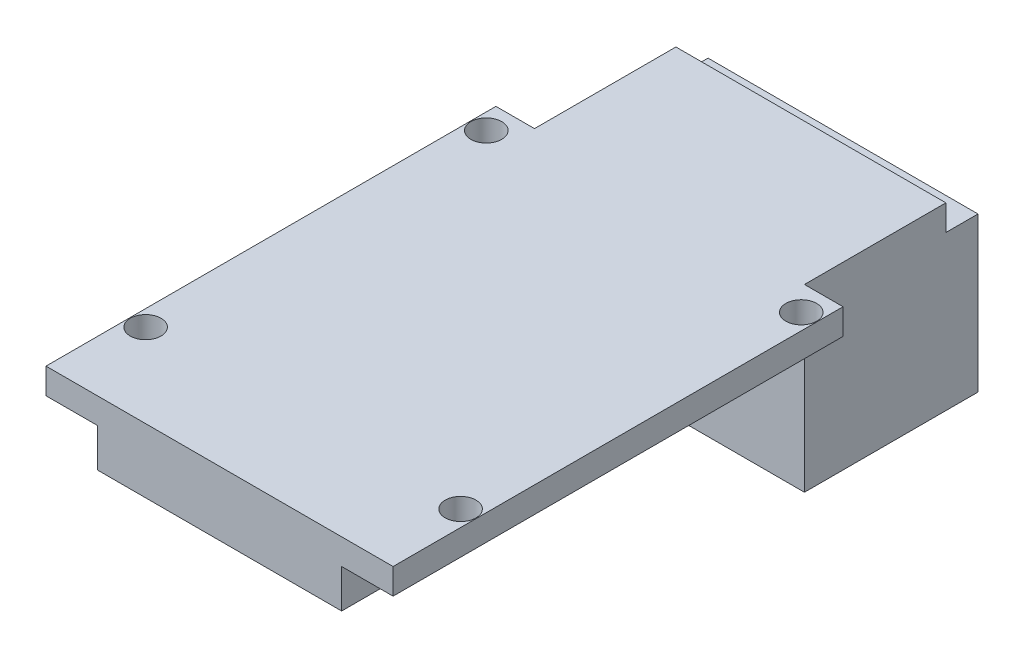
SolidWorks part; units mm, degrees
ref_plane "前视基准面" through (0, 0, 0) normal (0, 0, 1) x (1, 0, 0)
ref_plane "上视基准面" through (0, 0, 0) normal (0, 1, 0) x (1, 0, 0)
ref_plane "右视基准面" through (0, 0, 0) normal (1, 0, 0) x (0, 0, -1)
sketch "草图1" plane through (0, 0, 0) normal (0, 1, 0) x (1, 0, 0)
  line L0 (10.5, 17.5) -> (13.5, 17.5)
  line L1 (-13.5, -17.5) -> (13.5, -17.5)
  line L2 (-13.5, -17.5) -> (-13.5, 17.5)
  line L3 (-13.5, 17.5) -> (-10.5, 17.5)
  line L4 (13.5, -17.5) -> (13.5, 17.5)
  line L5 (-13.5, -17.5) -> (13.5, 17.5) construction
  line L6 (-13.5, 17.5) -> (13.5, -17.5) construction
  line L7 (-10.5, 28.5) -> (10.5, 28.5)
  line L8 (-10.5, 28.5) -> (-10.5, 17.5)
  line L9 (0, 0) -> (0, 9.2823) construction
  line L10 (10.5, 28.5) -> (10.5, 17.5)
  line L11 (-10.5, 28.5) -> (10.5, 17.5) construction
  line L12 (-10.5, 17.5) -> (10.5, 28.5) construction
  circle A0 centre (12.25, -11) radius 1.2
  circle A1 centre (12.25, 15.5) radius 1.2
  circle A2 centre (-12.25, 15.5) radius 1.2
  circle A3 centre (-12.25, -11) radius 1.2
  point P0 (0, 0)
  point P6 (0, 23)
  point P17 (10.5, 15.2819)
  point P18 (0, 0)
  point P19 (0, 0)
  point P21 (11.3276, 17.5)
  dimension "D5" = 2.4
  dimension "D1" = 27
  dimension "D2" = 35
  dimension "D3" = 11
  dimension "D4" = 21
  dimension "D6" = 26.5
  dimension "D7" = 2
  dimension "D8" = 24.5
extrude "凸台-拉伸1" add sketch "草图1" along normal blind 2
sketch "草图2" plane through (0, 0, 0) normal (0, -1, 0) x (1, 0, 0)
  line L0 (10.5, -28.5) -> (-10.5, -28.5) construction
  line L1 (10.5, -31) -> (-10.5, -31)
  line L2 (10.5, -31) -> (10.5, -17.5)
  line L3 (10.5, -17.5) -> (-10.5, -17.5)
  line L4 (-10.5, -31) -> (-10.5, -17.5)
  line L5 (10.5, -31) -> (-10.5, -17.5) construction
  line L6 (10.5, -17.5) -> (-10.5, -31) construction
  line L7 (10.5, -17.5) -> (10.5, -28.5) construction
  point P0 (0, -24.25)
  dimension "D1" = 2.5
extrude "凸台-拉伸2" add sketch "草图2" along normal blind 12
sketch "草图3" plane through (0, 0, -31) normal (0, 0, -1) x (-1, 0, 0)
  line L2 (10.5, 0) -> (-10.5, 0) construction
  circle A0 centre (0, -6) radius 4
  point P2 (0, 0)
  point P5 (0, -5.7522)
  dimension "D1" = 8
  dimension "D2" = 6
extrude "切除-拉伸1" cut sketch "草图3" against normal blind 4
sketch "草图4" plane through (0, 0, 0) normal (0, -1, 0) x (1, 0, 0)
  line L0 (-13.5, 17.5) -> (13.5, 17.5) construction
  line L1 (9.5, 13.5) -> (-9.5, 13.5)
  line L2 (9.5, 13.5) -> (9.5, 17.5)
  line L3 (9.5, 17.5) -> (-9.5, 17.5)
  line L4 (-9.5, 13.5) -> (-9.5, 17.5)
  line L5 (9.5, 13.5) -> (-9.5, 17.5) construction
  line L6 (9.5, 17.5) -> (-9.5, 13.5) construction
  point P0 (0, 15.5)
  point P7 (0, 0)
  dimension "D1" = 4
  dimension "D2" = 19
extrude "凸台-拉伸3" add sketch "草图4" along normal blind 3
sketch "草图5" plane through (0, 0, 0) normal (0, -1, 0) x (1, 0, 0)
  circle A0 centre (-3.2742, 1.8475) radius 6
  point P2 (-3.2742, 1.8475)
  dimension "D1" = 12
extrude "凸台-拉伸4" add sketch "草图5" along normal blind 5
